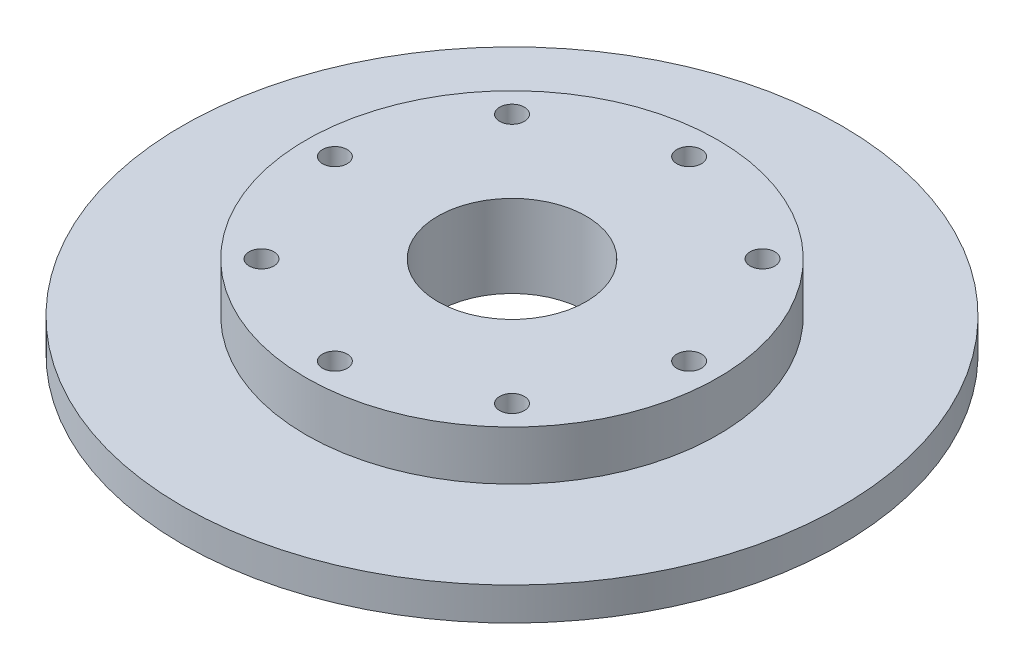
SolidWorks part; units mm, degrees
ref_plane "Front Plane" through (0, 0, 0) normal (0, 0, 1) x (1, 0, 0)
ref_plane "Top Plane" through (0, 0, 0) normal (0, 1, 0) x (1, 0, 0)
ref_plane "Right Plane" through (0, 0, 0) normal (1, 0, 0) x (0, 0, -1)
sketch "Sketch1" plane through (0, 0, 0) normal (0, 1, 0) x (1, 0, 0)
  circle A0 centre (0, 0) radius 40
  dimension "D1" = 80
extrude "Boss-Extrude1" add sketch "Sketch1" along normal blind 4
sketch "Sketch2" plane through (0, 4, 0) normal (0, 1, 0) x (1, 0, 0)
  circle A0 centre (0, 0) radius 25
  dimension "D1" = 50
extrude "Boss-Extrude2" add sketch "Sketch2" along normal blind 6
sketch "Sketch3" plane through (0, 10, 0) normal (0, 1, 0) x (1, 0, 0)
  circle A0 centre (0, 0) radius 21.5 construction
  circle A1 centre (0, -21.5) radius 1.5
  circle A2 centre (-15.2028, -15.2028) radius 1.5
  circle A3 centre (-21.5, 0) radius 1.5
  circle A4 centre (-15.2028, 15.2028) radius 1.5
  circle A5 centre (0, 21.5) radius 1.5
  circle A6 centre (15.2028, 15.2028) radius 1.5
  circle A7 centre (21.5, 0) radius 1.5
  circle A8 centre (15.2028, -15.2028) radius 1.5
  point P21 (0, 0)
  dimension "D1" = 43
  dimension "D2" = 3
extrude "Cut-Extrude1" cut sketch "Sketch3" against normal blind 5
sketch "Sketch4" plane through (0, 10, 0) normal (0, 1, 0) x (1, 0, 0)
  circle A0 centre (0, 0) radius 9
  dimension "D1" = 18
extrude "Cut-Extrude2" cut sketch "Sketch4" against normal through all
sketch "Sketch5" plane through (0, 5, 0) normal (0, 1, 0) x (1, 0, 0)
  circle A1 centre (15.2028, 15.2028) radius 1.5 construction
  circle A2 centre (-15.2028, -15.2028) radius 1.5 construction
  circle A3 centre (15.2028, 15.2028) radius 1.5
  circle A4 centre (-15.2028, -15.2028) radius 1.5
extrude "Cut-Extrude3" cut sketch "Sketch5" against normal through all
sketch "Sketch6" plane through (0, 0, 0) normal (0, -1, 0) x (1, 0, 0)
  circle A0 centre (-15.2028, 15.2028) radius 2.84
  circle A1 centre (15.2028, -15.2028) radius 2.84
  dimension "D1" = 5.68
  dimension "D2" = 5.68
extrude "Cut-Extrude4" cut sketch "Sketch6" against normal blind 3
